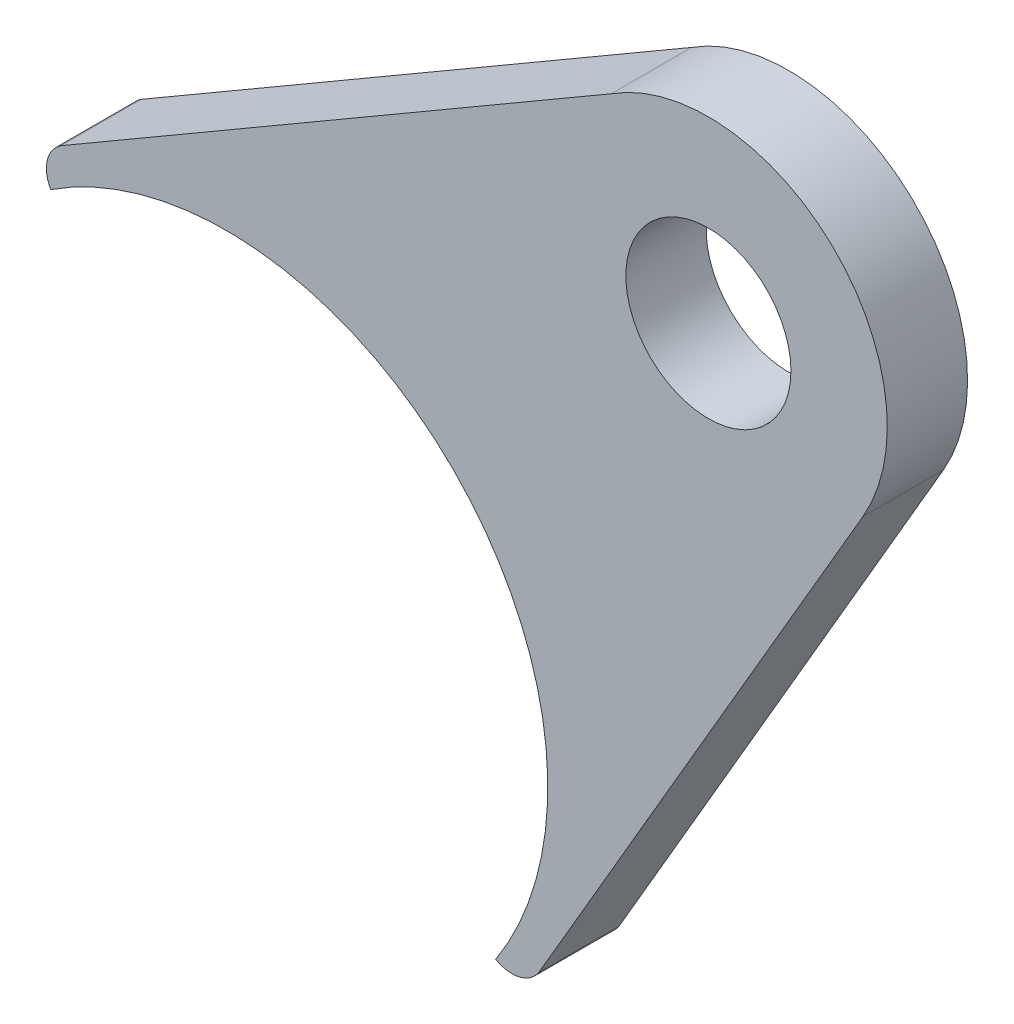
SolidWorks part; units mm, degrees
ref_plane "Front Plane" through (0, 0, 0) normal (0, 0, 1) x (1, 0, 0)
ref_plane "Top Plane" through (0, 0, 0) normal (0, 1, 0) x (1, 0, 0)
ref_plane "Right Plane" through (0, 0, 0) normal (1, 0, 0) x (0, 0, -1)
sketch "Sketch1" plane through (0, 0, 0) normal (0, 0, 1) x (1, 0, 0)
  line L4 (-6.5491, 12.3333) -> (15.2029, 24.9863)
  line L5 (12.3489, -6.5253) -> (25.1637, 15.4915)
  arc A0 (10.6407, -6.9329) -> (-6.9547, 10.6265) centre (0, 0) ccw
  circle A1 centre (19.05, 19.05) radius 3.2639
  arc A3 (10.6407, -6.9329) -> (12.3489, -6.5253) centre (11.2818, -5.8366) ccw
  arc A4 (25.1637, 15.4915) -> (15.2029, 24.9863) centre (19.05, 19.05) ccw
  arc A5 (-6.9547, 10.6265) -> (-6.5491, 12.3333) centre (-5.8584, 11.2675) cw
  dimension "D1" = 25.4
  dimension "D2" = 6.5278
  dimension "D5" = 14.1478
  dimension "D6" = 1.27
  dimension "D7" = 1.27
  dimension "D3" = 19.05
  dimension "D4" = 19.05
extrude "Boss-Extrude1" add sketch "Sketch1" along normal blind 3.175
